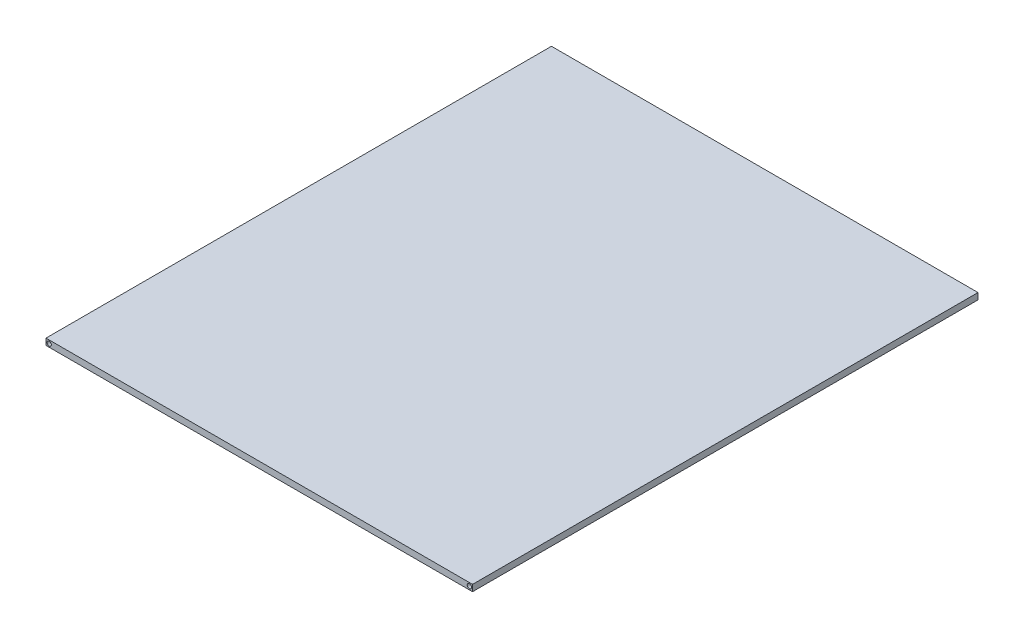
SolidWorks part; units mm, degrees
ref_plane "Front Plane" through (0, 0, 0) normal (0, 0, 1) x (1, 0, 0)
ref_plane "Top Plane" through (0, 0, 0) normal (0, 1, 0) x (1, 0, 0)
ref_plane "Right Plane" through (0, 0, 0) normal (1, 0, 0) x (0, 0, -1)
sketch "Sketch1" plane through (0, 0, 0) normal (0, 1, 0) x (1, 0, 0)
  line L1 (0, 0) -> (200, 0)
  line L2 (0, 0) -> (0, -237)
  line L3 (0, -237) -> (200, -237)
  line L4 (200, 0) -> (200, -237)
  dimension "D1" = 200
  dimension "D2" = 237
extrude "Boss-Extrude1" add sketch "Sketch1" along normal blind 3
ref_plane "Plane1" through (0, 0, 118.5) normal (0, 0, -1) x (-1, 0, 0)
ref_plane "Plane2" through (100, 0, 0) normal (-1, 0, 0) x (0, 0, 1)
sketch "Sketch4" plane through (0, 0, 237) normal (0, 0, 1) x (1, 0, 0)
  line L0 (200, 3) -> (200, 0) construction
  line L1 (0, 3) -> (0, 0) construction
  circle A0 centre (1.5, 1.5) radius 0.9951
  circle A1 centre (198.5, 1.5) radius 1
  dimension "D1" = 2
  dimension "D2" = 1.5
  dimension "D3" = 1.5
extrude "Cut-Extrude1" cut sketch "Sketch4" against normal blind 10
mirror "Mirror1" about plane through (0, 0, 118.5) normal (0, 0, -1) of "Cut-Extrude1"
